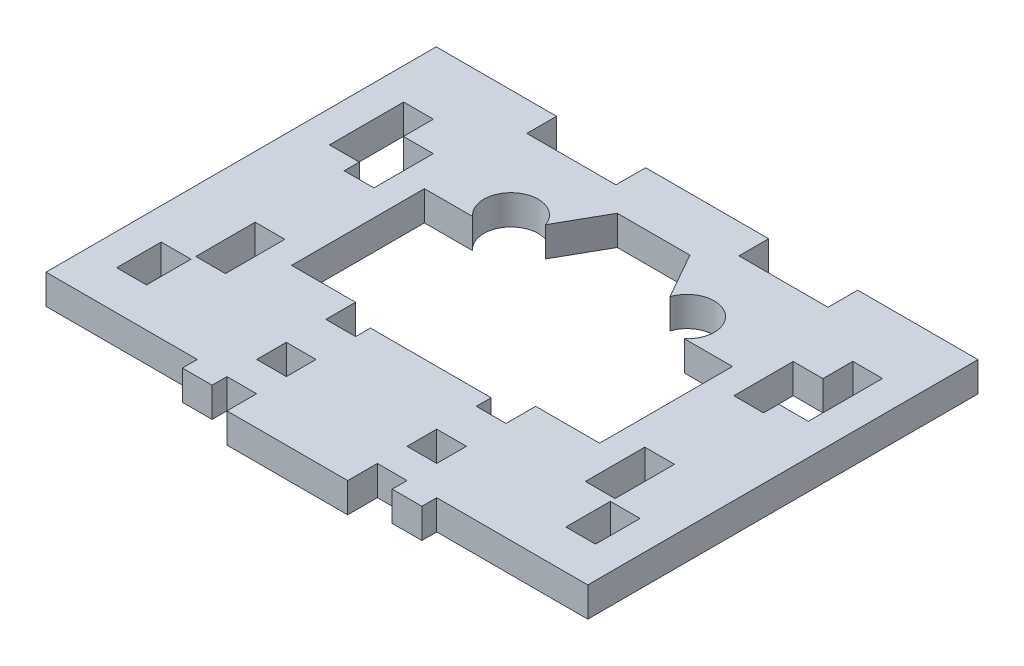
SolidWorks part; units mm, degrees
ref_plane "Front Plane" through (0, 0, 0) normal (0, 0, 1) x (1, 0, 0)
ref_plane "Top Plane" through (0, 0, 0) normal (0, 1, 0) x (1, 0, 0)
ref_plane "Right Plane" through (0, 0, 0) normal (1, 0, 0) x (0, 0, -1)
sketch "Sketch1" plane through (0, 0, 0) normal (0, 1, 0) x (1, 0, 0)
  line L0 (36.3736, 2.3857) -> (42.3736, 2.3857)
  line L1 (-54.7706, 33.3797) -> (-30.4571, 33.3797)
  line L2 (-54.7706, 33.3797) -> (-54.7706, -45.4885)
  line L3 (-54.7706, -45.4885) -> (-24.1979, -45.4885)
  line L4 (54.7236, 33.3797) -> (54.7236, -45.4885)
  line L5 (-48.3971, 5.4257) -> (-48.3971, -28.5743) construction
  line L6 (-7.3496, 22.5489) -> (-18.2214, 3.3388)
  line L7 (-7.3496, 22.5489) -> (7.3261, 22.5489)
  line L8 (-18.2214, 3.3388) -> (-18.2214, -25.4885)
  line L9 (-18.2214, -25.4885) -> (-12.1979, -25.4885)
  line L10 (18.1979, 3.3388) -> (18.1979, -25.4885)
  line L11 (7.3261, 22.5489) -> (18.1979, 3.3388)
  line L12 (15.92, 7.3638) -> (31.1168, 7.3638)
  line L13 (-42.3736, -27.6143) -> (-42.3736, -15.6143)
  line L14 (-42.3736, -15.6143) -> (-36.3736, -15.6143)
  line L15 (-42.3736, -27.6143) -> (-36.3736, -27.6143)
  line L16 (-36.3736, -15.6143) -> (-36.3736, -27.6143)
  line L17 (-42.3736, 2.3857) -> (-36.3736, 2.3857)
  line L18 (-42.3736, 2.3857) -> (-42.3736, 5.4257)
  line L19 (-42.3971, 14.3857) -> (-36.3736, 14.3857)
  line L20 (-36.3736, 2.3857) -> (-36.3736, 14.3857)
  line L21 (36.3736, 14.3857) -> (42.3736, 14.3857)
  line L22 (36.3736, 14.3857) -> (36.3736, 2.3857)
  line L23 (42.3736, 2.3857) -> (42.3736, 5.4257)
  line L24 (-36.3736, 2.3857) -> (-36.3736, -15.6143) construction
  line L25 (36.3736, -15.6143) -> (42.3736, -15.6143)
  line L26 (36.3736, -15.6143) -> (36.3736, -27.6143)
  line L27 (36.3736, -27.6143) -> (42.3736, -27.6143)
  line L28 (42.3736, -15.6143) -> (42.3736, -27.6143)
  line L29 (-18.1979, -33.4885) -> (-12.1979, -33.4885)
  line L30 (-18.1979, -33.4885) -> (-18.1979, -39.4885)
  line L31 (-18.1979, -39.4885) -> (-12.1979, -39.4885)
  line L32 (-12.1979, -33.4885) -> (-12.1979, -39.4885)
  line L33 (12.1979, -33.4885) -> (18.1979, -33.4885)
  line L34 (12.1979, -33.4885) -> (12.1979, -39.4885)
  line L35 (12.1979, -39.4885) -> (18.1979, -39.4885)
  line L36 (18.1979, -33.4885) -> (18.1979, -39.4885)
  line L37 (30.4101, 33.3797) -> (54.7236, 33.3797)
  line L38 (-30.4571, 33.3797) -> (-30.4571, 27.3797)
  line L39 (-30.4571, 27.3797) -> (-12.4571, 27.3797)
  line L40 (-12.4571, 33.3797) -> (-12.4571, 27.3797)
  line L41 (-30.4571, 27.3797) -> (-54.7706, 27.3797) construction
  line L42 (12.4101, 33.3797) -> (12.4101, 27.3797)
  line L43 (12.4101, 27.3797) -> (30.4101, 27.3797)
  line L44 (30.4101, 33.3797) -> (30.4101, 27.3797)
  line L45 (42.3736, -28.5743) -> (48.3736, -28.5743)
  line L46 (42.3736, -28.5743) -> (42.3736, -37.5743)
  line L47 (42.3736, -37.5743) -> (48.3736, -37.5743)
  line L48 (48.3736, -28.5743) -> (48.3736, -37.5743)
  line L49 (42.3736, 5.4257) -> (48.3736, 5.4257)
  line L50 (42.3736, 14.3857) -> (42.3736, 20.4257)
  line L51 (42.3736, 20.4257) -> (48.3736, 20.4257)
  line L52 (48.3736, 5.4257) -> (48.3736, 20.4257)
  line L53 (-42.3736, 5.4257) -> (-48.3971, 5.4257)
  line L54 (-42.3971, 14.3857) -> (-42.3971, 20.4257)
  line L55 (-42.3971, 20.4257) -> (-48.3971, 20.4257)
  line L56 (-48.3971, 5.4257) -> (-48.3971, 20.4257)
  line L57 (-42.3736, -28.5743) -> (-48.3971, -28.5743)
  line L58 (-42.3736, -28.5743) -> (-42.3736, -37.5743)
  line L59 (-42.3736, -37.5743) -> (-48.3971, -37.5743)
  line L60 (-48.3971, -28.5743) -> (-48.3971, -37.5743)
  line L61 (31.1168, 7.3638) -> (31.1168, -19.4885)
  line L62 (-15.9435, 7.3638) -> (-31.1403, 7.3638)
  line L63 (-31.1403, 7.3638) -> (-31.1403, -19.4885)
  line L64 (-42.3971, 20.4257) -> (42.3736, 20.4257) construction
  line L65 (-18.1979, -39.4885) -> (-42.3736, -39.4885) construction
  line L66 (18.1979, -39.4885) -> (42.3736, -39.4885) construction
  line L67 (12.1979, -33.4885) -> (12.1979, -25.4885) construction
  line L68 (-7.3496, 22.5489) -> (-42.3971, 22.5489) construction
  line L69 (7.3261, 22.5489) -> (42.3736, 22.5489) construction
  line L70 (31.1168, -19.4885) -> (18.1979, -19.4885)
  line L71 (-31.1403, -19.4885) -> (-18.2214, -19.4885)
  line L72 (-48.3971, 20.4257) -> (-48.3971, 33.3797) construction
  line L73 (-36.3736, 14.3857) -> (-36.3736, 33.3797) construction
  line L74 (12.1979, -39.4885) -> (12.1979, -45.4885) construction
  line L75 (-12.4571, 33.3797) -> (12.4101, 33.3797)
  line L76 (30.4101, 27.3797) -> (54.7236, 27.3797) construction
  line L77 (20.6783, -19.4885) -> (20.6783, -25.4885) construction
  line L78 (31.1168, -19.4885) -> (31.1168, -28.5743) construction
  line L79 (42.3736, -37.5743) -> (31.1168, -37.5743) construction
  line L80 (12.1979, -25.4885) -> (12.1979, -22.4885)
  line L81 (12.1979, -22.4885) -> (-12.1979, -22.4885)
  line L82 (-12.1979, -22.4885) -> (-12.1979, -25.4885)
  line L83 (12.1979, -25.4885) -> (18.1979, -25.4885)
  line L84 (-12.1979, -45.4885) -> (-12.1979, -51.4885)
  line L85 (-12.1979, -51.4885) -> (12.1979, -51.4885)
  line L86 (12.1979, -51.4885) -> (12.1979, -45.4885)
  line L87 (18.1979, -45.4885) -> (18.1979, -48.4885)
  line L88 (18.1979, -48.4885) -> (24.1979, -48.4885)
  line L89 (24.1979, -48.4885) -> (24.1979, -45.4885)
  line L90 (-18.1979, -45.4885) -> (-18.1979, -48.4885)
  line L91 (-18.1979, -48.4885) -> (-24.1979, -48.4885)
  line L92 (-24.1979, -48.4885) -> (-24.1979, -45.4885)
  line L93 (-18.1979, -45.4885) -> (-12.1979, -45.4885)
  line L94 (12.1979, -45.4885) -> (18.1979, -45.4885)
  line L95 (24.1979, -45.4885) -> (54.7236, -45.4885)
  circle A0 centre (17.7919, 11.5148) radius 5.5
  circle A1 centre (-17.7919, 11.5148) radius 5.5
  dimension "D2" = 6.35
  dimension "D5" = 6
extrude "Boss-Extrude1" add sketch "Sketch1" along normal blind 6 contours L1 L44 L43 L42 L40 L39 L38 L2 L3 L4 L60 L57 L58 L59 L45 L48 L47 L46 L29 L32 L31 L30 L14 L16 L15 L13 L7 L10 L9 L8 L25 L28 L27 L26 L33 L36 L35 L34 L52 L49 L23
